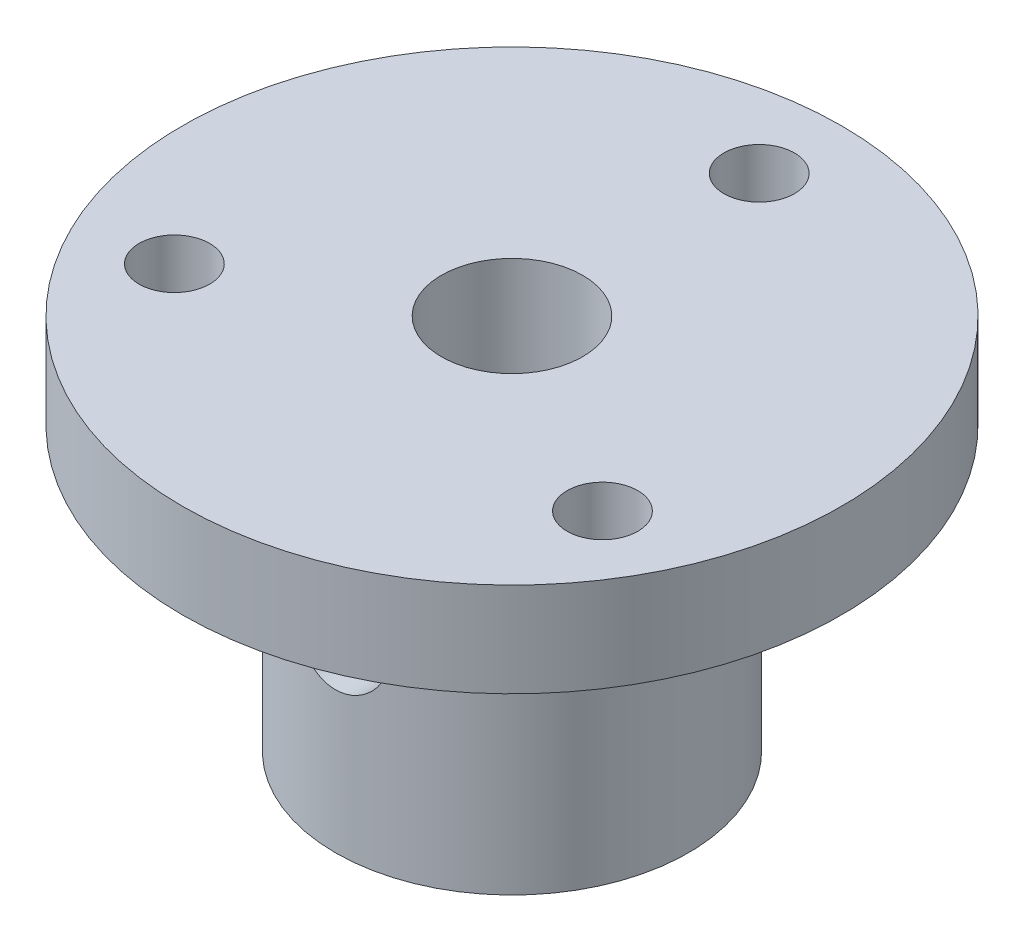
SolidWorks part; units mm, degrees
ref_plane "Plan de face" through (0, 0, 0) normal (0, 0, 1) x (1, 0, 0)
ref_plane "Plan de dessus" through (0, 0, 0) normal (0, 1, 0) x (1, 0, 0)
ref_plane "Plan de droite" through (0, 0, 0) normal (1, 0, 0) x (0, 0, -1)
sketch "Esquisse1" plane through (0, 0, 0) normal (0, 0, 1) x (1, 0, 0)
  line L0 (-3, 0) -> (-3, 16)
  line L1 (-3, 16) -> (-14, 16)
  line L2 (-14, 16) -> (-14, 12)
  line L3 (-14, 12) -> (-7.5, 12)
  line L4 (-7.5, 12) -> (-7.5, 0)
  line L5 (-7.5, 0) -> (-3, 0)
  line L6 (0, 0) -> (0, 21.267) construction
  dimension "D1" = 3
  dimension "D2" = 16
  dimension "D3" = 14
  dimension "D4" = 12
  dimension "D5" = 7.5
revolve "Révolution1" add sketch "Esquisse1" angle 360 about L6
sketch "Esquisse2" plane through (0, 16, 0) normal (0, 1, 0) x (1, 0, 0)
  line L0 (9.0933, -5.25) -> (0, 0) construction
  line L1 (0, 0) -> (0, 10.5) construction
  line L2 (0, 0) -> (-9.0933, -5.25) construction
  circle A0 centre (0, 0) radius 10.5 construction
  circle A1 centre (9.0933, -5.25) radius 1.5
  circle A2 centre (-9.0933, -5.25) radius 1.5
  circle A3 centre (0, 10.5) radius 1.5
  dimension "D1" = 21
  dimension "D2" = 3
  dimension "D4" = 120
  dimension "D5" = 120
extrude "Enlèv. mat.-Extru.1" cut sketch "Esquisse2" against normal through all
sketch "Esquisse3" plane through (0, 0, 0) normal (0, 0, 1) x (1, 0, 0)
  line L0 (-7.5, 0) -> (7.5, 0) construction
  circle A0 centre (0, 8) radius 2
  dimension "D1" = 4
  dimension "D2" = 8
extrude "Enlèv. mat.-Extru.2" cut sketch "Esquisse3" along normal through all
